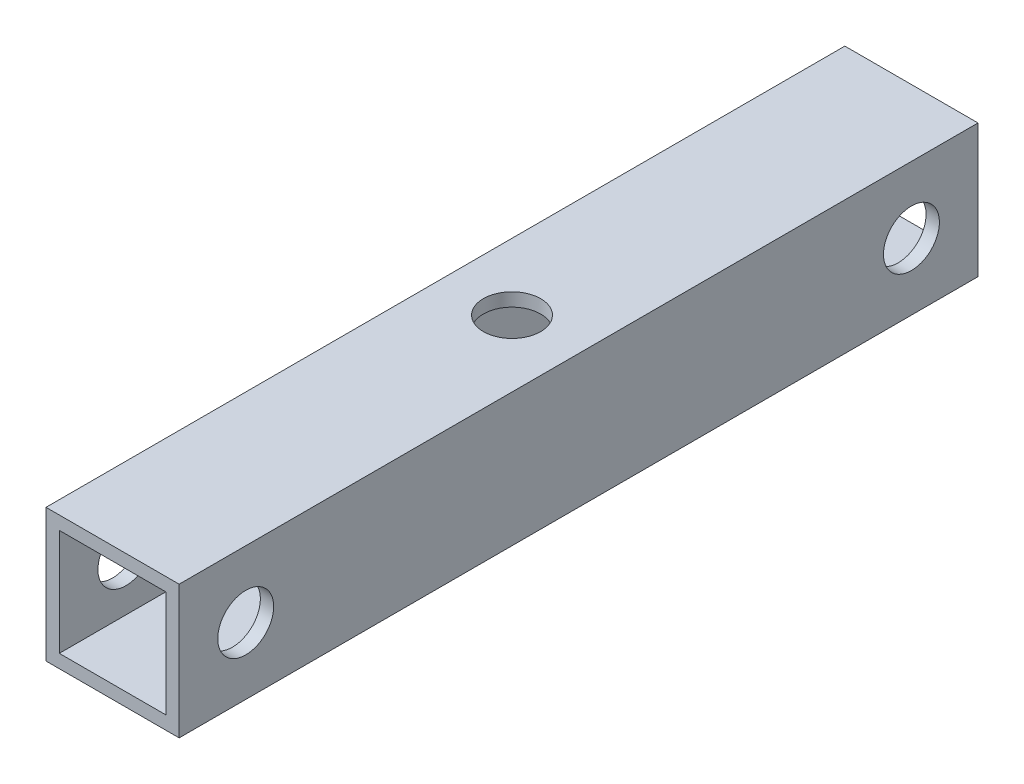
SolidWorks part; units mm, degrees
material "5052-H34"
ref_plane "正面" through (0, 0, 0) normal (0, 0, 1) x (1, 0, 0)
ref_plane "平面" through (0, 0, 0) normal (0, 1, 0) x (1, 0, 0)
ref_plane "右側面" through (0, 0, 0) normal (1, 0, 0) x (0, 0, -1)
sketch "ｽｹｯﾁ1" plane through (0, 0, 0) normal (0, 0, 1) x (1, 0, 0)
  line L1 (0, 0) -> (10, 0)
  line L2 (0, 0) -> (0, 10)
  line L3 (0, 10) -> (10, 10)
  line L4 (10, 0) -> (10, 10)
  dimension "D1" = 10
  dimension "D2" = 10
extrude "押し出し-薄板1" add sketch "ｽｹｯﾁ1" along normal blind 60 thin thin type one direction reverse wall 1
sketch "ｽｹｯﾁ2" plane through (10, 0, 0) normal (1, 0, 0) x (0, 0, -1)
  line L0 (-60, 5) -> (0, 5) construction
  line L1 (-60, 0) -> (-60, 10) construction
  line L2 (0, 0) -> (0, 10) construction
  line L3 (-30, 10) -> (-30, 0) construction
  line L4 (-60, 10) -> (0, 10) construction
  line L5 (-60, 0) -> (0, 0) construction
  circle A0 centre (-55, 5) radius 2.1
  circle A2 centre (-5, 5) radius 2.1
  dimension "D1" = 4.2
  dimension "D2" = 5
extrude "ｶｯﾄ - 押し出し1" cut sketch "ｽｹｯﾁ2" against normal up to surface (10 mm away) up to face at (0, 5, 30)
sketch "ｽｹｯﾁ3" plane through (0, 10, 0) normal (0, 1, 0) x (1, 0, 0)
  line L0 (5, 0) -> (5, -60) construction
  line L1 (10, 0) -> (0, 0) construction
  line L2 (10, -60) -> (0, -60) construction
  line L3 (10, -30) -> (0, -30) construction
  line L4 (10, -60) -> (10, 0) construction
  line L5 (0, -60) -> (0, 0) construction
  circle A2 centre (5, -30) radius 2.15
  dimension "D1" = 4.3
extrude "ｶｯﾄ - 押し出し2" cut sketch "ｽｹｯﾁ3" against normal up to surface (10 mm away) up to face at (5, 0, 30)
